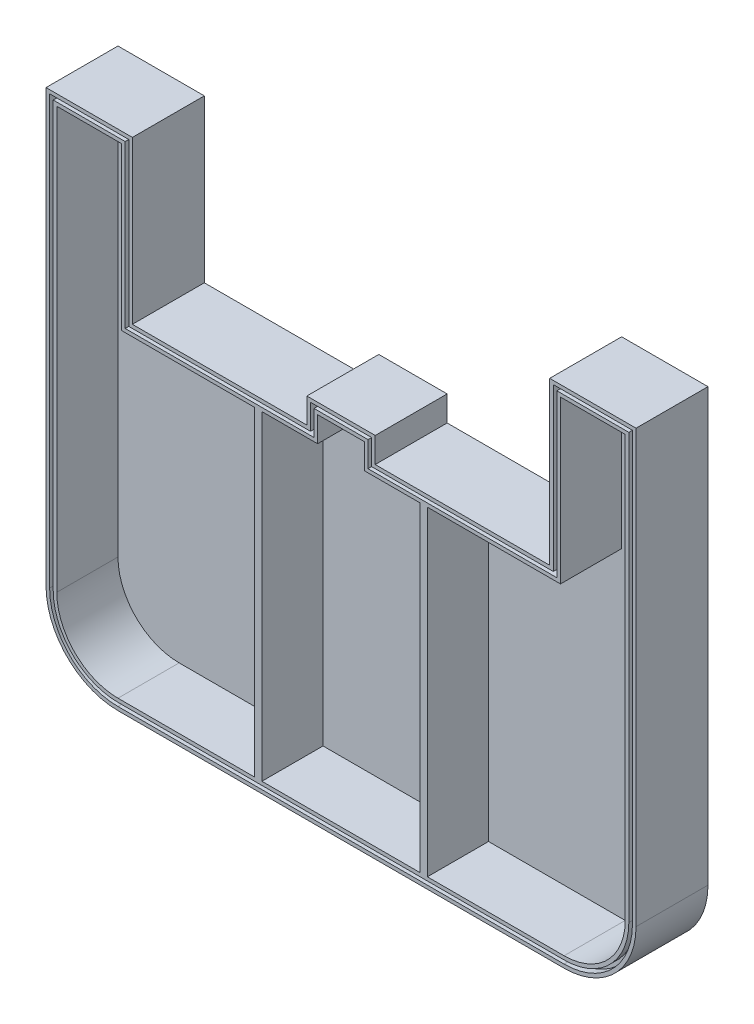
SolidWorks part; units mm, degrees
ref_plane "Plano frontal" through (0, 0, 0) normal (0, 0, 1) x (1, 0, 0)
ref_plane "Plano superior" through (0, 0, 0) normal (0, 1, 0) x (1, 0, 0)
ref_plane "Plano direito" through (0, 0, 0) normal (1, 0, 0) x (0, 0, -1)
sketch "Esboço1" plane through (0, 0, 0) normal (0, 0, 1) x (1, 0, 0)
  line L12 (-58, 23) -> (-58, 68)
  line L13 (-58, 68) -> (-82, 68)
  line L14 (-82, 68) -> (-82, -52)
  line L15 (-62, -72) -> (62, -72)
  line L16 (82, -52) -> (82, 68)
  line L17 (58, 68) -> (82, 68)
  line L18 (58, 23) -> (58, 68)
  line L21 (-9.5, 30) -> (9.5, 30)
  line L22 (-9.5, 23) -> (-9.5, 30)
  line L23 (-9.5, 23) -> (-58, 23)
  line L24 (9.5, 30) -> (9.5, 23)
  line L25 (9.5, 23) -> (58, 23)
  arc A0 (-82, -52) -> (-62, -72) centre (-62, -52) ccw
  arc A1 (62, -72) -> (82, -52) centre (62, -52) ccw
  dimension "D1" = 20
  dimension "D2" = 120
  dimension "D3" = 120
extrude "Ressalto-extrusão1" add sketch "Esboço1" along normal blind 20
shell "Casca1" thickness 3
sketch "Esboço2" plane through (0, 0, 3) normal (0, 0, 1) x (1, 0, 0)
  line L0 (-24, -69) -> (-22, -69)
  line L1 (-6.5, 20) -> (-61, 20) construction
  line L2 (22, -69) -> (24, -69)
  line L3 (61, 20) -> (6.5, 20) construction
  line L4 (-22, 20) -> (-22, -69)
  line L5 (-62, -69) -> (62, -69) construction
  line L6 (22, 20) -> (22, -69)
  line L7 (-62, -69) -> (62, -69) construction
  line L8 (-22, 20) -> (-24, 20)
  line L9 (-6.5, 20) -> (-61, 20) construction
  line L10 (-24, 20) -> (-24, -69)
  line L11 (22, 20) -> (24, 20)
  line L12 (24, 20) -> (24, -69)
  dimension "D1" = 22
  dimension "D2" = 22
  dimension "D3" = 2
  dimension "D4" = 2
extrude "Ressalto-extrusão2" add sketch "Esboço2" along normal blind 17
sketch "Esboço3" plane through (0, 0, 3) normal (0, 0, 1) x (1, 0, 0)
  line L0 (70, 65) -> (70, 55)
  line L1 (79, 65) -> (61, 65) construction
  circle A0 centre (70, 55) radius 4
  dimension "D2" = 8
  dimension "D1" = 10
extrude "Corte-extrusão1" cut sketch "Esboço3" against normal through all
sketch "Esboço4" plane through (0, 0, 3) normal (0, 0, 1) x (1, 0, 0)
  line L0 (-70, 65) -> (-70, 55)
  line L1 (-61, 65) -> (-79, 65) construction
  circle A0 centre (-70, 55) radius 4
  dimension "D2" = 8
  dimension "D1" = 10
extrude "Corte-extrusão2" cut sketch "Esboço4" against normal blind 44
sketch "Esboço5" plane through (0, 0, 20) normal (0, 0, 1) x (1, 0, 0)
  line L13 (-62, -70) -> (62, -70)
  line L14 (80, -52) -> (80, 66)
  line L15 (80, 66) -> (60, 66)
  line L16 (60, 66) -> (60, 21)
  line L17 (60, 21) -> (7.5, 21)
  line L18 (7.5, 21) -> (7.5, 28)
  line L19 (7.5, 28) -> (-7.5, 28)
  line L20 (-7.5, 28) -> (-7.5, 21)
  line L21 (-7.5, 21) -> (-60, 21)
  line L22 (-60, 21) -> (-60, 66)
  line L23 (-60, 66) -> (-80, 66)
  line L24 (-8.5, 22) -> (-59, 22)
  line L25 (-59, 22) -> (-59, 67)
  line L26 (-59, 67) -> (-81, 67)
  line L27 (-81, 67) -> (-81, -52)
  line L28 (-62, -71) -> (62, -71)
  line L29 (81, -52) -> (81, 67)
  line L30 (81, 67) -> (59, 67)
  line L31 (59, 67) -> (59, 22)
  line L32 (59, 22) -> (8.5, 22)
  line L33 (8.5, 22) -> (8.5, 29)
  line L34 (8.5, 29) -> (-8.5, 29)
  line L35 (-8.5, 29) -> (-8.5, 22)
  line L36 (-8.5, 22) -> (-59, 22)
  line L37 (-59, 22) -> (-59, 67)
  line L38 (-59, 67) -> (-81, 67)
  line L39 (-81, 67) -> (-81, -52)
  line L40 (-62, -71) -> (62, -71)
  line L41 (81, -52) -> (81, 67)
  line L42 (81, 67) -> (59, 67)
  line L43 (59, 67) -> (59, 22)
  line L44 (59, 22) -> (8.5, 22)
  line L45 (8.5, 22) -> (8.5, 29)
  line L46 (8.5, 29) -> (-8.5, 29)
  line L47 (-8.5, 29) -> (-8.5, 22)
  line L48 (-80, 66) -> (-80, -52)
  arc A2 (-80, -52) -> (-62, -70) centre (-62, -52) ccw
  arc A3 (62, -70) -> (80, -52) centre (62, -52) ccw
  arc A4 (-81, -52) -> (-62, -71) centre (-62, -52) ccw
  arc A5 (62, -71) -> (81, -52) centre (62, -52) ccw
  arc A6 (-81, -52) -> (-62, -71) centre (-62, -52) ccw
  arc A7 (62, -71) -> (81, -52) centre (62, -52) ccw
  dimension "D1" = 1
  dimension "D2" = 1
extrude "Corte-extrusão3" cut sketch "Esboço5" against normal blind 2
